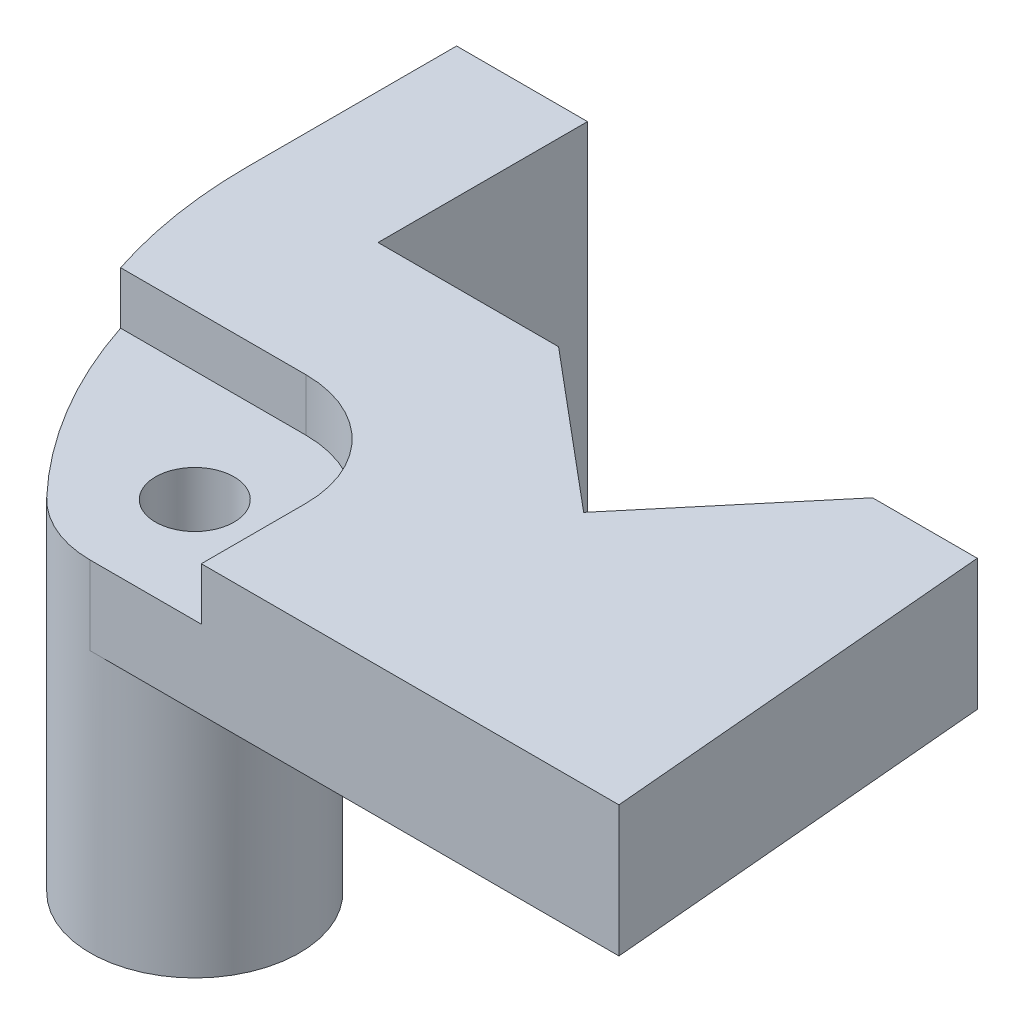
SolidWorks part; units mm, degrees
ref_plane "Front Plane" through (0, 0, 0) normal (0, 0, 1) x (1, 0, 0)
ref_plane "Top Plane" through (0, 0, 0) normal (0, 1, 0) x (1, 0, 0)
ref_plane "Right Plane" through (0, 0, 0) normal (1, 0, 0) x (0, 0, -1)
sketch "Sketch1" plane through (0, 0, 0) normal (0, 1, 0) x (1, 0, 0)
  line L0 (0, 32.3882) -> (0, 7) construction
  line L1 (0, 7) -> (6, 7) construction
  line L2 (6, 7) -> (39, 22.3882) construction
  line L3 (39, 22.3882) -> (72, 7) construction
  line L4 (72, 7) -> (78, 7) construction
  line L5 (78, 7) -> (78, 32.3882) construction
  line L6 (78, 32.3882) -> (0, 32.3882) construction
  line L7 (-11, 14) -> (-11, 22)
  line L8 (11.8877, 15) -> (15.8877, 15)
  line L9 (-3, 0) -> (17.2, 0)
  line L10 (17.5, 15.9916) -> (17.5, 0.8497) construction
  line L11 (17.2, 0) -> (15.8877, 15)
  line L12 (11.8877, 15) -> (6.8531, 9)
  line L13 (0.8943, 14) -> (-6, 14)
  line L14 (-11, 22) -> (-6, 22)
  line L15 (-6, 22) -> (-6, 14)
  line L17 (0.8943, 14) -> (6.8531, 9)
  line L19 (-3, 4) -> (-3, 0) construction
  circle A0 centre (-3, 4) radius 1.5
  circle A1 centre (-3, 4) radius 4 construction
  circle A2 centre (39, -0.5) radius 21 construction
  circle A3 centre (18.4662, -10) radius 21 construction
  arc A4 (-11, 14) -> (-5.8966, 1.2414) centre (7.5, 14) ccw
  arc A5 (-3, 0) -> (-5.8966, 1.2414) centre (-3, 4) cw
  dimension "D5" = 3
  dimension "D11" = 8
  dimension "D13" = 42
  dimension "D3" = 130
  dimension "D23" = 4
  dimension "D24" = 8
  dimension "D1" = 6
  dimension "D2" = 78
  dimension "D4" = 10
  dimension "D6" = 7
  dimension "D7" = 3
  dimension "D8" = 85
  dimension "D9" = 20.2
  dimension "D10" = 17.5
  dimension "D12" = 15
  dimension "D14" = 4
  dimension "D15" = 3
  dimension "D16" = 50
  dimension "D17" = 4
  dimension "D18" = 14
  dimension "D19" = 0.5
  dimension "D20" = 22
  dimension "D21" = 5
  dimension "D22" = 9
  dimension "D25" = 10
  dimension "D27" = 90
extrude "Boss-Extrude1" add sketch "Sketch1" along normal blind 5
sketch "Sketch2" plane through (0, 0, 0) normal (0, -1, 0) x (1, 0, 0)
  line L3 (-11, -14) -> (-11, -22)
  line L4 (-11, -22) -> (-6, -22)
  line L5 (-6, -22) -> (-6, -8)
  line L6 (-6, -8) -> (-3, -8)
  line L7 (-11, -22) -> (-11, -14) construction
  arc A0 (-3, 0) -> (-3, -8) centre (-3, -4) cw
  circle A1 centre (-3, -4) radius 1.5
  arc A2 (-3, 0) -> (-5.8966, -1.2414) centre (-3, -4) ccw
  arc A3 (-5.8966, -1.2414) -> (-11, -14) centre (7.5, -14) ccw construction
  arc A4 (-5.8966, -1.2414) -> (-11, -14) centre (7.5, -14) ccw
  dimension "D2" = 3
extrude "Boss-Extrude2" add sketch "Sketch2" along normal blind 10
sketch "Sketch3" plane through (0, 5, 0) normal (0, 1, 0) x (1, 0, 0)
  line L0 (1.25, 4) -> (1.25, 0)
  line L1 (-3, 0) -> (17.2, 0) construction
  line L2 (1.25, 0) -> (-10.0837, 0)
  line L3 (-10.0837, 0) -> (-10.0837, 8.25)
  line L4 (-10.0837, 8.25) -> (-3, 8.25)
  arc A0 (-3, 8.25) -> (1.25, 4) centre (-3, 4) cw
  arc A1 (-11, 14) -> (-5.8966, 1.2414) centre (7.5, 14) ccw construction
  dimension "D1" = 4.25
extrude "Cut-Extrude1" cut sketch "Sketch3" against normal blind 2 contours L4 A0 L0 L2 L3
sketch "Sketch4" plane through (0, -10, 0) normal (0, -1, 0) x (1, 0, 0)
  circle A0 centre (-3, -4) radius 4
extrude "Cut-Extrude2" cut sketch "Sketch4" against normal blind 2 flip side to cut
